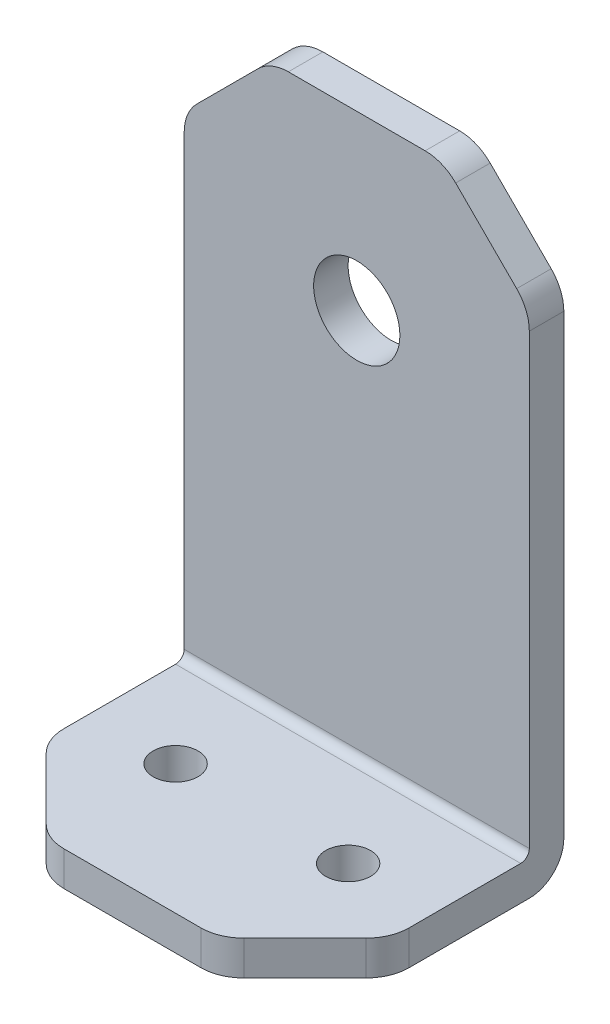
SolidWorks part; units mm, degrees
ref_plane "前基準面" through (0, 0, 0) normal (0, 0, 1) x (1, 0, 0)
ref_plane "上基準面" through (0, 0, 0) normal (0, 1, 0) x (1, 0, 0)
ref_plane "右基準面" through (0, 0, 0) normal (1, 0, 0) x (0, 0, -1)
sketch "草圖1" plane through (0, 0, 0) normal (0, 1, 0) x (1, 0, 0)
  line L1 (-20, -15) -> (20, -15)
  line L2 (-20, -15) -> (-20, 15)
  line L3 (-20, 15) -> (20, 15)
  line L4 (20, -15) -> (20, 15)
  line L5 (-20, -15) -> (20, 15) construction
  line L6 (-20, 15) -> (20, -15) construction
  point P0 (0, 0)
  dimension "D1" = 40
  dimension "D2" = 30
extrude "填料-伸長1" add sketch "草圖1" along normal blind 4
sketch "草圖3" plane through (0, 4, 0) normal (0, 1, 0) x (1, 0, 0)
  line L0 (20, -15) -> (20, 15) construction
  line L1 (-20, 15) -> (20, 15)
  line L2 (-20, 15) -> (-20, 11)
  line L3 (-20, 11) -> (20, 11)
  line L4 (20, 15) -> (20, 11)
  dimension "D1" = 4
extrude "填料-伸長2" add sketch "草圖3" along normal blind 65
fillet "圓角1" radius 4 1 edges at (0, 0, -15)
sketch "草圖4" plane through (0, 4, 0) normal (0, 1, 0) x (1, 0, 0)
  line L0 (20, 0) -> (-20, 0) construction
  line L3 (20, -15) -> (20, 11) construction
  line L4 (-20, 11) -> (-20, -15) construction
  line L5 (-20, -15) -> (20, -15) construction
  circle A0 centre (-10, 0) radius 2.6
  point P9 (0, 0)
  dimension "D1" = 5.2
  dimension "D2" = 10
  dimension "D3" = 15
extrude "除料-伸長1" cut sketch "草圖4" against normal through all
pattern_linear "直線複製排列1" count 2 spacing 20 along (1, 0, 0) of "除料-伸長1"
sketch "草圖5" plane through (0, 0, -11) normal (0, 0, 1) x (1, 0, 0)
  line L0 (0, 69) -> (0, 49) construction
  line L1 (-20, 69) -> (20, 69) construction
  circle A0 centre (0, 49) radius 5
  dimension "D1" = 10
  dimension "D2" = 20
extrude "除料-伸長2" cut sketch "草圖5" against normal through all
chamfer "導角1" distance 10 angle 45 4 edges at (20, 69, -13) (-20, 69, -13) (-20, 2, 15) (20, 2, 15)
fillet "圓角2" radius 5 8 edges at (20, 2, 5) (10, 2, 15) (-10, 2, 15) (-20, 2, 5) (20, 59, -13) (10, 69, -13) (-10, 69, -13) (-20, 59, -13)
fillet "圓角3" radius 1 1 edges at (0, 4, -11)
